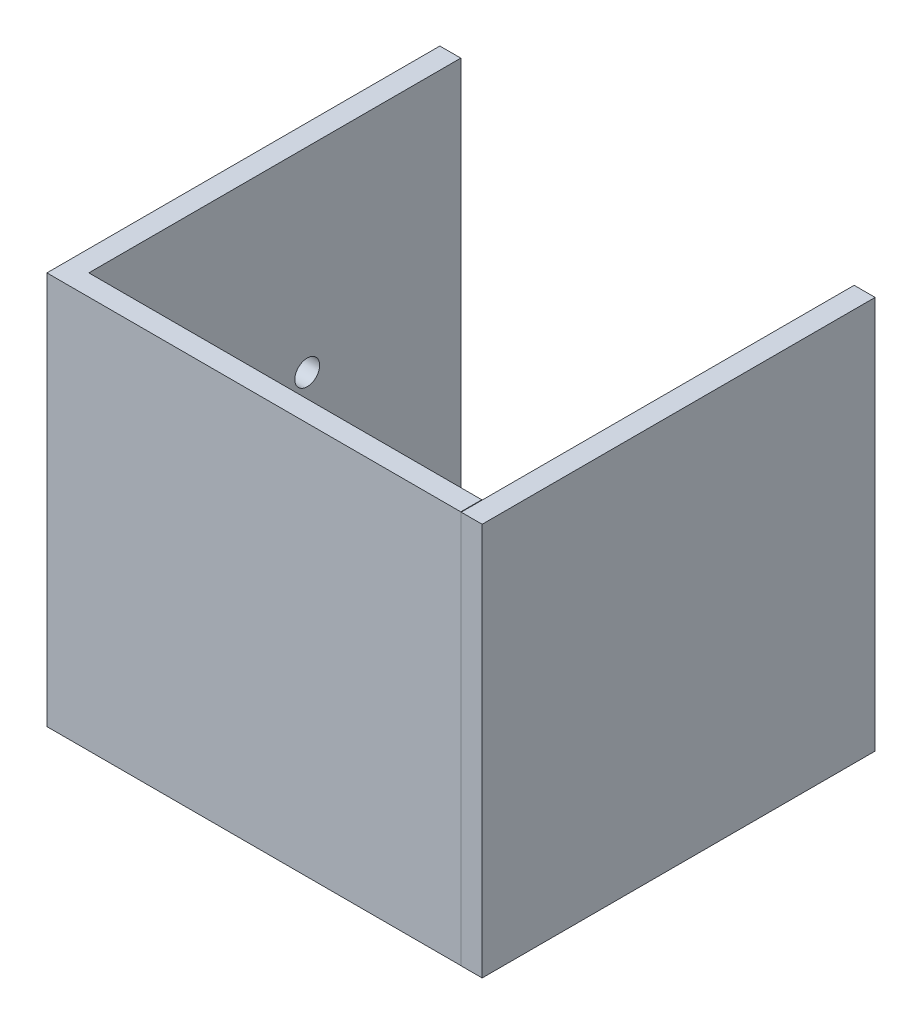
SolidWorks part; units mm, degrees
ref_plane "Front Plane" through (0, 0, 0) normal (0, 0, 1) x (1, 0, 0)
ref_plane "Top Plane" through (0, 0, 0) normal (0, 1, 0) x (1, 0, 0)
ref_plane "Right Plane" through (0, 0, 0) normal (1, 0, 0) x (0, 0, -1)
sketch "Sketch1" plane through (0, 0, 0) normal (0, 0, 1) x (1, 0, 0)
  line L1 (-75, 75) -> (75, 75)
  line L2 (-75, 75) -> (-75, -75)
  line L3 (-75, -75) -> (75, -75)
  line L4 (75, 75) -> (75, -75)
  line L5 (-75, 75) -> (75, -75) construction
  line L6 (-75, -75) -> (75, 75) construction
  point P0 (0, 0)
  dimension "D1" = 150
  dimension "D2" = 150
extrude "Boss-Extrude1" add sketch "Sketch1" along normal blind 8
sketch "Sketch2" plane through (0, 0, 0) normal (0, 0, -1) x (-1, 0, 0)
  line L0 (0, 0) -> (0, 75) construction
  line L1 (-75, 75) -> (75, 75) construction
  line L2 (0, 0) -> (0, -75) construction
  line L3 (75, -75) -> (-75, -75) construction
  line L4 (0, 0) -> (75, 0) construction
  line L5 (75, 75) -> (75, -75) construction
  line L6 (0, 0) -> (-75, 0) construction
  line L7 (-75, -75) -> (-75, 75) construction
ref_plane "Plane2" through (75, 0, 0) normal (1, 0, 0) x (0, 0, -1)
sketch "Sketch3" plane through (75, 0, 0) normal (1, 0, 0) x (0, 0, -1)
  line L1 (-7.8503, 74.8173) -> (142.1497, 74.8173)
  line L2 (-7.8503, 74.8173) -> (-7.8503, -75.1827)
  line L3 (-7.8503, -75.1827) -> (142.1497, -75.1827)
  line L4 (142.1497, 74.8173) -> (142.1497, -75.1827)
  dimension "D1" = 150
  dimension "D2" = 150
extrude "Boss-Extrude2" add sketch "Sketch3" along normal blind 8
ref_plane "Plane3" through (-75, 0, 0) normal (-1, 0, 0) x (0, 0, 1)
sketch "Sketch4" plane through (-75, 0, 0) normal (-1, 0, 0) x (0, 0, 1)
  line L0 (-142.0575, 0.4088) -> (7.6596, 0.5854) construction
  line L1 (8, 75) -> (-142, 75)
  line L2 (8, 75) -> (8, -75)
  line L3 (8, -75) -> (-142, -75)
  line L4 (-142, 75) -> (-142, -75)
  line L5 (-67.3755, 75.4439) -> (-67.3755, -73.9201) construction
  circle A2 centre (-83.3822, 0.4202) radius 4.7432
  dimension "D1" = 150
  dimension "D2" = 150
extrude "Boss-Extrude3" add sketch "Sketch4" along normal blind 8
